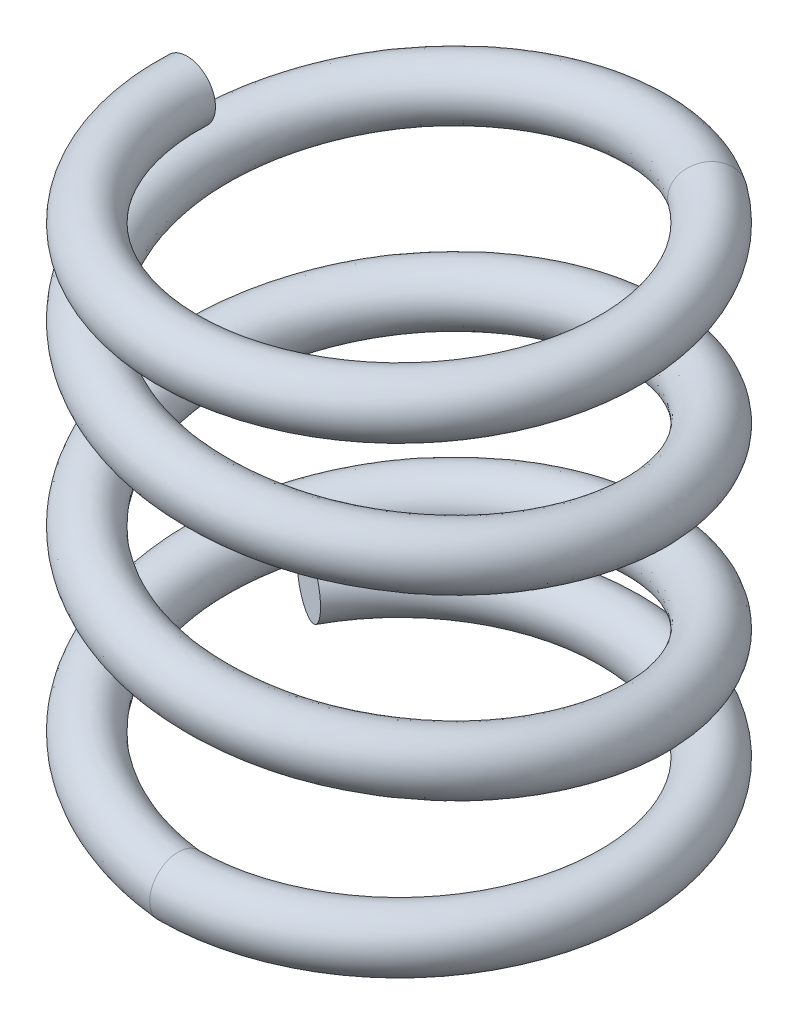
SolidWorks part; units mm, degrees
ref_plane "Front Plane" through (0, 0, 0) normal (0, 0, 1) x (1, 0, 0)
ref_plane "Top Plane" through (0, 0, 0) normal (0, 1, 0) x (1, 0, 0)
ref_plane "Right Plane" through (0, 0, 0) normal (1, 0, 0) x (0, 0, -1)
sketch "Sketch1" plane through (0, 0, 0) normal (0, 1, 0) x (1, 0, 0)
  circle A0 centre (0, 0) radius 3.1
  dimension "D1" = 6.2
curve "Helix/Spiral1" pitch 2.5 height 6.5 turns 2.6
sketch "Sketch3" plane through (0, 0, 0) normal (1, 0, 0) x (0, 0, -1)
  circle A0 centre (-3.1, 0) radius 0.4
  spline S0 degree 3 poles (-3.1, 0) (-3.1, 0.0525) (-2.9338, 0.1587) (-2.2248, 0.317) (-1.1672, 0.4756) (0.0732, 0.6341) (1.3021, 0.7927) (2.3271, 0.9512) (2.9874, 1.1098) (3.1798, 1.2683) (2.8739, 1.4268) (2.1178, 1.5854) (1.0299, 1.7439) (-0.2193, 1.9024) (-1.4342, 2.061) (-2.4244, 2.2195) (-3.0348, 2.378) (-3.1697, 2.5366) (-2.808, 2.6951) (-2.0064, 2.8537) (-0.8904, 3.0122) (0.3651, 3.1707) (1.5633, 3.3293) (2.5166, 3.4878) (3.0757, 3.6463) (3.1529, 3.8049) (2.7361, 3.9634) (1.8907, 4.122) (0.749, 4.2805) (-0.51, 4.439) (-1.6891, 4.5976) (-2.6036, 4.7561) (-3.1101, 4.9146) (-3.1294, 5.0732) (-2.6585, 5.2317) (-1.771, 5.3902) (-0.606, 5.5488) (0.6539, 5.7073) (1.8113, 5.8659) (2.685, 6.0244) (3.1378, 6.183) (3.1001, 6.3413) (2.7484, 6.4475) (2.508, 6.5) knots 0 0 0 0 0.02439 0.04878 0.073171 0.097561 0.121951 0.146341 0.170732 0.195122 0.219512 0.243902 0.268293 0.292683 0.317073 0.341463 0.365854 0.390244 0.414634 0.439024 0.463415 0.487805 0.512195 0.536585 0.560976 0.585366 0.609756 0.634146 0.658537 0.682927 0.707317 0.731707 0.756098 0.780488 0.804878 0.829268 0.853659 0.878049 0.902439 0.926829 0.95122 0.97561 1 1 1 1 construction
  dimension "D1" = 0.8
sweep "Sweep2" add profiles "Sketch3" path "Helix/Spiral1"
sketch "Sketch7" plane through (0, 0, 0) normal (0, 1, 0) x (1, 0, 0)
  line L0 (0, -3.5) -> (0, -2.7) construction
  arc A0 (0, -3.1) -> (-2.7314, 1.4662) centre (0, 0) ccw
  dimension "D1" = 6.2
sketch "Sketch8" plane through (0, 0, 0) normal (1, 0, 0) x (0, 0, -1)
  line L0 (3.1, 0) -> (-3.1, 0) construction
  circle A0 centre (-3.1, 0) radius 0.4
sweep "Sweep3" add profiles "Sketch8" path "Sketch7"
sketch "Sketch10" plane through (0, 0, 0) normal (0.809, 0, 0.5878) x (0.5878, 0, -0.809)
  circle A0 centre (3.1, 6.5) radius 0.4
  circle A1 centre (3.1, 6.5) radius 0.4 construction
  point P2 (3.1, 6.5)
ref_plane "Plane1" through (0, 6.5, 0) normal (0, 1, 0) x (1, 0, 0)
sketch "Sketch12" plane through (0, 6.5, 0) normal (0, 1, 0) x (1, 0, 0)
  arc A0 (1.8221, 2.508) -> (-3.0969, 0.1388) centre (0, 0) cw
  point P5 (-3, 1)
  point P6 (-3, 0)
sweep "Sweep4" add profiles "Sketch10" path "Sketch12"
sketch "Sketch4" plane through (0, 0, 0) normal (1, 0, 0) x (0, 0, -1)
  line L0 (0.3739, 6.9) -> (0.1389, 6.9) construction
  line L1 (-3.1, -0.4) -> (-4.5425, -0.4) construction
  circle A3 centre (-3.1, 0) radius 0.4 construction
  ellipse E0 centre (0.1388, 6.5) end of major axis (0.1388, 6.1) minor radius 0.0179 construction
  point P4 (-2, 9)
  point P5 (0, 0)
sketch "Sketch5" plane through (0, 0, 0) normal (0, 1, 0) x (1, 0, 0)
  circle A0 centre (0, 0) radius 3.5 construction
  circle A1 centre (0, 0) radius 2.7 construction
  circle A2 centre (0, 0) radius 3.1 construction
  dimension "D1" = 7
  dimension "D2" = 6.2
  dimension "D3" = 5.4
